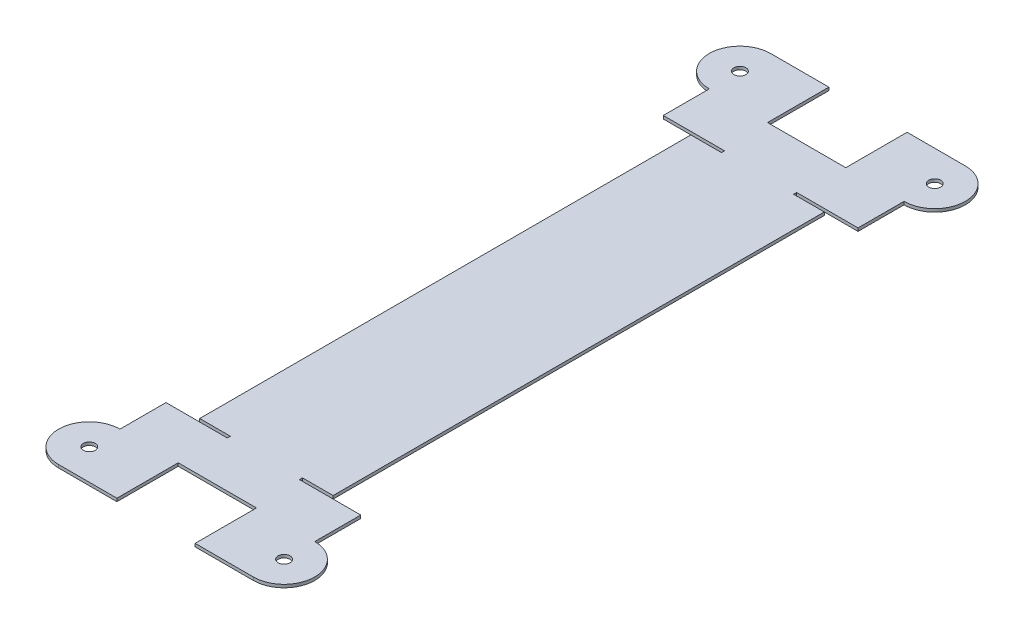
SolidWorks part; units mm, degrees
ref_plane "Front Plane" through (0, 0, 0) normal (0, 0, 1) x (1, 0, 0)
ref_plane "Top Plane" through (0, 0, 0) normal (0, 1, 0) x (1, 0, 0)
ref_plane "Right Plane" through (0, 0, 0) normal (1, 0, 0) x (0, 0, -1)
sketch "Sketch1" plane through (0, 0, 0) normal (0, 1, 0) x (1, 0, 0)
  line L0 (-31.75, 116.066) -> (-12.75, 116.066)
  line L1 (-11.75, 126.066) -> (11.75, 126.066) construction
  line L2 (-11.75, 126.066) -> (-11.75, -126.066) construction
  line L3 (-11.75, -126.066) -> (11.75, -126.066) construction
  line L4 (11.75, 126.066) -> (11.75, -126.066) construction
  line L5 (-11.75, 126.066) -> (11.75, -126.066) construction
  line L6 (-11.75, -126.066) -> (11.75, 126.066) construction
  line L7 (31.75, -106.066) -> (-31.75, -106.066) construction
  line L8 (31.75, -106.066) -> (31.75, 106.066) construction
  line L9 (31.75, 106.066) -> (-31.75, 106.066) construction
  line L10 (-31.75, -106.066) -> (-31.75, 106.066) construction
  line L11 (31.75, -106.066) -> (-31.75, 106.066) construction
  line L12 (31.75, 106.066) -> (-31.75, -106.066) construction
  line L13 (-12.75, 116.066) -> (-12.75, 96.066)
  line L14 (-12.75, 96.066) -> (-11.75, 96.066)
  line L15 (-11.75, 96.066) -> (-11.75, 126.066) construction
  line L16 (-11.75, 126.066) -> (-6, 126.066) construction
  line L17 (-6, 126.066) -> (-6, 118.066) construction
  line L18 (-6, 118.066) -> (-0.5, 118.066) construction
  line L19 (6, 118.066) -> (6, 126.066) construction
  line L20 (6, 126.066) -> (11.75, 126.066) construction
  line L21 (0, 126.066) -> (0, 118.066) construction
  line L22 (-0.5, 118.066) -> (-0.5, 108.066) construction
  line L23 (-0.5, 108.066) -> (0.5, 108.066) construction
  line L24 (0.5, 108.066) -> (0.5, 118.066) construction
  line L25 (0, 108.066) -> (0, 118.066) construction
  line L26 (0.5, 118.066) -> (6, 118.066) construction
  line L27 (-0.5, 118.066) -> (0, 118.066) construction
  line L28 (0, 118.066) -> (0.5, 118.066) construction
  line L29 (0, 0) -> (11.75, 0) construction
  line L30 (-31.75, 96.066) -> (-31.75, 81.066)
  line L31 (-31.75, 81.066) -> (-11.75, 81.066)
  line L32 (-11.75, 81.066) -> (-11.75, 80.066)
  line L33 (-11.75, 80.066) -> (-21.75, 80.066)
  line L34 (-21.75, 80.066) -> (-21.75, -80.066)
  line L35 (-21.75, 0) -> (-11.75, 0) construction
  line L36 (11.75, 96.066) -> (11.75, 126.066) construction
  line L37 (12.75, 96.066) -> (11.75, 96.066)
  line L38 (12.75, 116.066) -> (12.75, 96.066)
  line L39 (31.75, 116.066) -> (12.75, 116.066)
  line L40 (31.75, 96.066) -> (31.75, 81.066)
  line L41 (31.75, 81.066) -> (11.75, 81.066)
  line L42 (11.75, 81.066) -> (11.75, 80.066)
  line L43 (11.75, 80.066) -> (21.75, 80.066)
  line L44 (21.75, 80.066) -> (21.75, -80.066)
  line L45 (21.75, 0) -> (11.75, 0) construction
  line L46 (11.75, -80.066) -> (21.75, -80.066)
  line L47 (11.75, -81.066) -> (11.75, -80.066)
  line L48 (31.75, -81.066) -> (11.75, -81.066)
  line L49 (31.75, -96.066) -> (31.75, -81.066)
  line L50 (31.75, -116.066) -> (12.75, -116.066)
  line L51 (12.75, -116.066) -> (12.75, -96.066)
  line L52 (12.75, -96.066) -> (11.75, -96.066)
  line L53 (11.75, -96.066) -> (11.75, -126.066) construction
  line L54 (6, -126.066) -> (11.75, -126.066) construction
  line L55 (6, -118.066) -> (6, -126.066) construction
  line L56 (0.5, -118.066) -> (6, -118.066) construction
  line L57 (0.5, -108.066) -> (0.5, -118.066) construction
  line L58 (-0.5, -108.066) -> (0.5, -108.066) construction
  line L59 (-0.5, -118.066) -> (-0.5, -108.066) construction
  line L60 (-6, -118.066) -> (-0.5, -118.066) construction
  line L61 (-6, -126.066) -> (-6, -118.066) construction
  line L62 (-11.75, -126.066) -> (-6, -126.066) construction
  line L63 (-11.75, -96.066) -> (-11.75, -126.066) construction
  line L64 (-12.75, -96.066) -> (-11.75, -96.066)
  line L65 (-12.75, -116.066) -> (-12.75, -96.066)
  line L66 (-31.75, -116.066) -> (-12.75, -116.066)
  line L67 (-31.75, -96.066) -> (-31.75, -81.066)
  line L68 (-31.75, -81.066) -> (-11.75, -81.066)
  line L69 (-11.75, -81.066) -> (-11.75, -80.066)
  line L70 (-11.75, -80.066) -> (-21.75, -80.066)
  line L71 (-11.75, 96.066) -> (11.75, 96.066)
  line L72 (-11.75, -96.066) -> (11.75, -96.066)
  circle A0 centre (-31.75, 106.066) radius 1.95
  arc A1 (-31.75, 116.066) -> (-31.75, 96.066) centre (-31.75, 106.066) ccw
  arc A8 (-31.75, 96.066) -> (-31.75, 116.066) centre (-31.75, 106.066) ccw construction
  circle A9 centre (31.75, 106.066) radius 1.95
  arc A10 (31.75, 116.066) -> (31.75, 96.066) centre (31.75, 106.066) cw
  arc A11 (31.75, 96.066) -> (31.75, 116.066) centre (31.75, 106.066) cw construction
  circle A12 centre (31.75, -106.066) radius 1.95
  arc A13 (31.75, -96.066) -> (31.75, -116.066) centre (31.75, -106.066) ccw construction
  arc A14 (31.75, -116.066) -> (31.75, -96.066) centre (31.75, -106.066) ccw
  circle A15 centre (-31.75, -106.066) radius 1.95
  arc A16 (-31.75, -116.066) -> (-31.75, -96.066) centre (-31.75, -106.066) cw
  arc A17 (-31.75, -96.066) -> (-31.75, -116.066) centre (-31.75, -106.066) cw construction
  point P0 (0, 0)
  point P18 (0, 0)
  dimension "D1" = 3.9
  dimension "D2" = 20
  dimension "D3" = 20
  dimension "D4" = 23.5
  dimension "D5" = 20
  dimension "D6" = 212.132
  dimension "D7" = 12
  dimension "D8" = 8
  dimension "D9" = 1
  dimension "D10" = 10
  dimension "D11" = 20
  dimension "D12" = 1
  dimension "D13" = 1
  dimension "D14" = 25
  dimension "D15" = 10
extrude "Boss-Extrude1" add sketch "Sketch1" along normal blind 1
